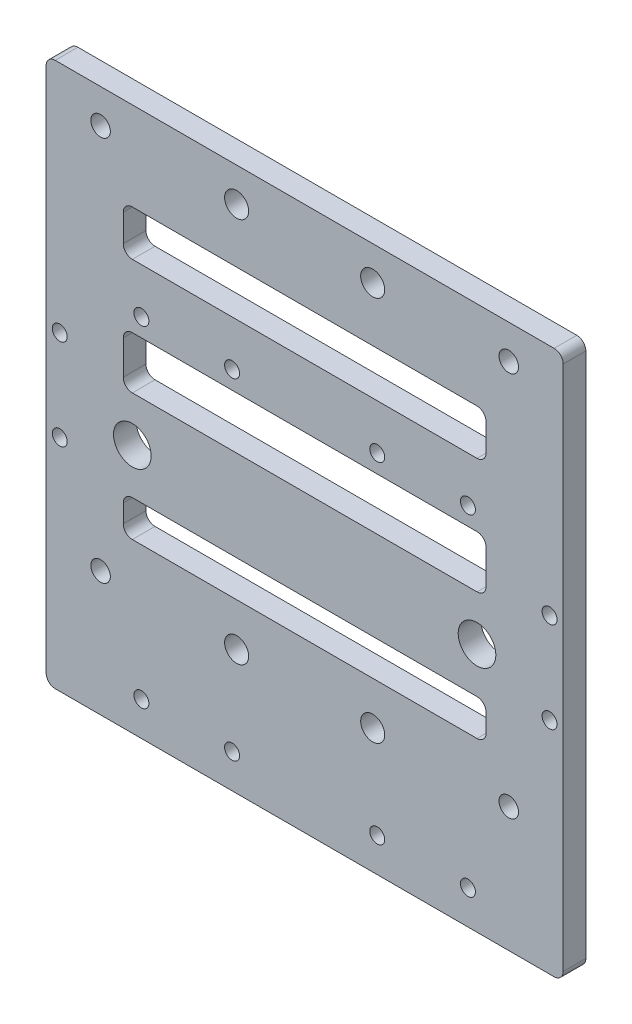
SolidWorks part; units mm, degrees
material "玻纤板"
ref_plane "前视基准面" through (0, 0, 0) normal (0, 0, 1) x (1, 0, 0)
ref_plane "上视基准面" through (0, 0, 0) normal (0, 1, 0) x (1, 0, 0)
ref_plane "右视基准面" through (0, 0, 0) normal (1, 0, 0) x (0, 0, -1)
other "Configuration Table"
sketch "草图1" plane through (0, 0, 0) normal (0, 0, 1) x (1, 0, 0)
  line L0 (0, 0) -> (0, -126.3816) construction
  line L1 (-57, 60) -> (57, 60)
  line L2 (-57, 60) -> (-57, -60)
  line L3 (-57, -60) -> (57, -60)
  line L4 (57, 60) -> (57, -60)
  line L5 (-57, 60) -> (57, -60) construction
  line L6 (-57, -60) -> (57, 60) construction
  circle A0 centre (-15, -32.5) radius 2.65
  circle A1 centre (15, -32.5) radius 2.65
  circle A2 centre (-45, -32.5) radius 2.15
  circle A3 centre (45, -32.5) radius 2.15
  circle A4 centre (-45, 52.5) radius 2.15
  circle A5 centre (-15, 52.5) radius 2.65
  circle A6 centre (15, 52.5) radius 2.65
  circle A7 centre (45, 52.5) radius 2.15
  point P0 (0, 0)
  dimension "D3" = 7.5
  dimension "D4" = 30
  dimension "D5" = 5.3
  dimension "D6" = 90
  dimension "D7" = 4.3
  dimension "D1" = 114
  dimension "D2" = 120
  dimension "D9" = 85
  dimension "D8" = 2
extrude "凸台-拉伸1" add sketch "草图1" along normal blind 5
sketch "草图2" plane through (0, 0, 5) normal (0, 0, 1) x (1, 0, 0)
  line L0 (0, 0) -> (0, 75.9687) construction
  line L2 (-16, -52.5) -> (-16, 20.5) construction
  circle A0 centre (-16, -52.5) radius 1.65
  circle A1 centre (-36, -52.5) radius 1.65
  circle A2 centre (16, -52.5) radius 1.65
  circle A3 centre (36, -52.5) radius 1.65
  circle A4 centre (-16, 20.5) radius 1.65
  circle A5 centre (-36, 20.5) radius 1.65
  circle A6 centre (16, 20.5) radius 1.65
  circle A7 centre (36, 20.5) radius 1.65
  circle A9 centre (45, -32.5) radius 2.15 construction
  dimension "D1" = 32
  dimension "D2" = 20
  dimension "D3" = 20
  dimension "D4" = 3.3
  dimension "D6" = 73
  dimension "D5" = 2
extrude "切除-拉伸1" cut sketch "草图2" against normal through all
sketch "草图3" plane through (0, 0, 5) normal (0, 0, 1) x (1, 0, 0)
  line L0 (0, 0) -> (0, 87.4973) construction
  circle A0 centre (-38, -5) radius 4.15
  circle A1 centre (38, -5) radius 4.15
  circle A2 centre (-45, -32.5) radius 2.15 construction
  dimension "D1" = 27.5
  dimension "D2" = 76
  dimension "D3" = 8.3
extrude "切除-拉伸2" cut sketch "草图3" against normal through all
sketch "草图5" plane through (0, 0, 5) normal (0, 0, 1) x (1, 0, 0)
  line L0 (0, 0) -> (0, 74.2891) construction
  line L1 (-50, -5) -> (50, -5)
  line L2 (-50, -5) -> (-50, -30)
  line L3 (-50, -30) -> (50, -30)
  line L4 (50, -5) -> (50, -30)
  dimension "D1" = 5
  dimension "D2" = 25
  dimension "D3" = 100
extrude "切除-拉伸3" [suppressed] cut sketch "草图5" against normal through all
sketch "草图6" plane through (0, 0, 5) normal (0, 0, 1) x (1, 0, 0)
  line L0 (57, -60) -> (57, 60) construction
  line L2 (0, 0) -> (0, 99.2654) construction
  circle A0 centre (54, -11.5) radius 1.65
  circle A1 centre (45, -32.5) radius 2.15 construction
  circle A2 centre (54, 8.5) radius 1.65
  circle A3 centre (-54, -11.5) radius 1.65
  circle A4 centre (-54, 8.5) radius 1.65
  dimension "D2" = 21
  dimension "D3" = 3.3
  dimension "D4" = 20
  dimension "D1" = 3
extrude "切除-拉伸4" cut sketch "草图6" against normal through all
sketch "草图7" plane through (0, 0, 5) normal (0, 0, 1) x (1, 0, 0)
  line L0 (0, 0) -> (0, 54.5278) construction
  line L1 (-40, 16.5) -> (40, 16.5)
  line L2 (-40, 16.5) -> (-40, 5)
  line L3 (-40, 5) -> (40, 5)
  line L4 (40, 16.5) -> (40, 5)
  line L6 (-40, 40.5) -> (40, 40.5)
  line L7 (-40, 40.5) -> (-40, 30.5)
  line L8 (-40, 30.5) -> (40, 30.5)
  line L9 (40, 40.5) -> (40, 30.5)
  line L10 (-40, -15) -> (40, -15)
  line L11 (-40, -15) -> (-40, -23)
  line L12 (-40, -23) -> (40, -23)
  line L13 (40, -15) -> (40, -23)
  circle A0 centre (38, -5) radius 4.15 construction
  circle A1 centre (36, 20.5) radius 1.65 construction
  dimension "D1" = 10
  dimension "D6" = 10
  dimension "D2" = 4
  dimension "D3" = 80
  dimension "D4" = 10
  dimension "D5" = 10
  dimension "D7" = 8
extrude "切除-拉伸5" cut sketch "草图7" against normal through all
fillet "圆角1" radius 2 16 edges at (40, 5, 2.5) (40, 16.5, 2.5) (-40, 16.5, 2.5) (-40, 5, 2.5) (40, -15, 2.5) (40, -23, 2.5) (-40, -23, 2.5) (-40, -15, 2.5) (40, 30.5, 2.5) (40, 40.5, 2.5) (-40, 40.5, 2.5) (-40, 30.5, 2.5) (57, -60, 2.5) (-57, -60, 2.5) (-57, 60, 2.5) (57, 60, 2.5)
